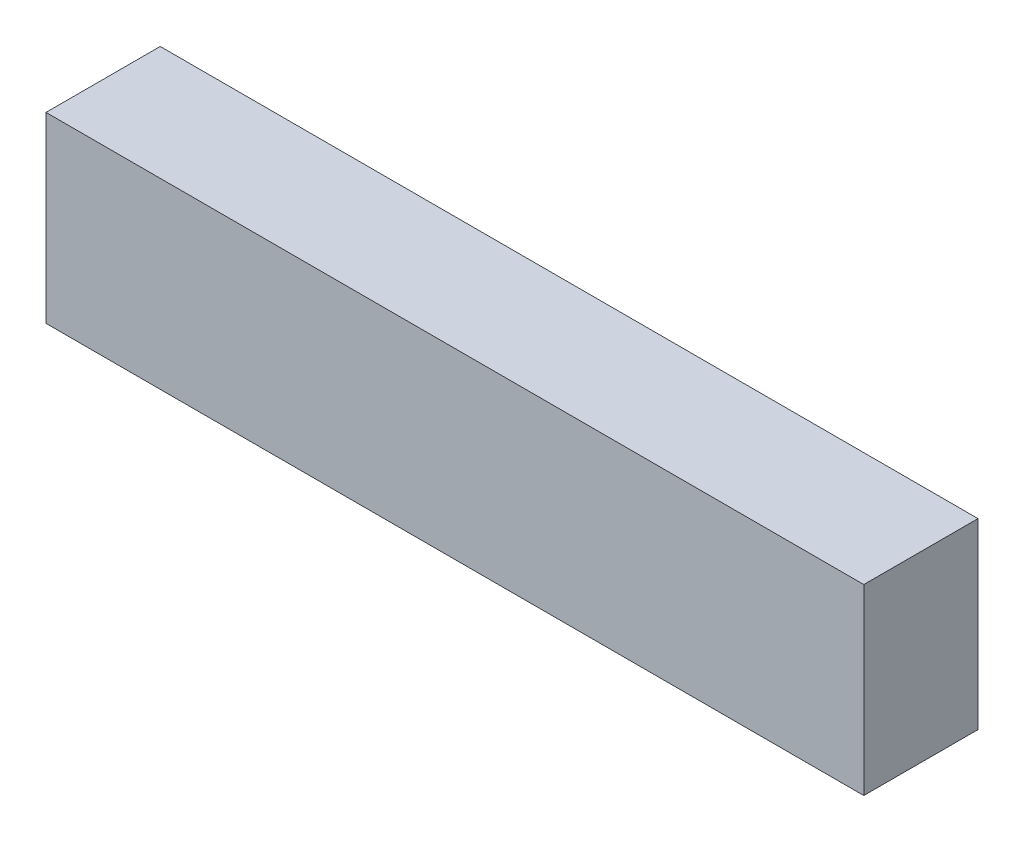
SolidWorks part; units mm, degrees
ref_plane "Plan de face" through (0, 0, 0) normal (0, 0, 1) x (1, 0, 0)
ref_plane "Plan de dessus" through (0, 0, 0) normal (0, 1, 0) x (1, 0, 0)
ref_plane "Plan de droite" through (0, 0, 0) normal (1, 0, 0) x (0, 0, -1)
sketch "Esquisse1" plane through (0, 0, 0) normal (0, 0, 1) x (1, 0, 0)
  line L1 (0, 0) -> (179, 0)
  line L2 (0, 0) -> (0, 40)
  line L3 (0, 40) -> (179, 40)
  line L4 (179, 0) -> (179, 40)
  dimension "D1" = 179
  dimension "D2" = 40
extrude "Boss.-Extru.1" add sketch "Esquisse1" along normal blind 25
